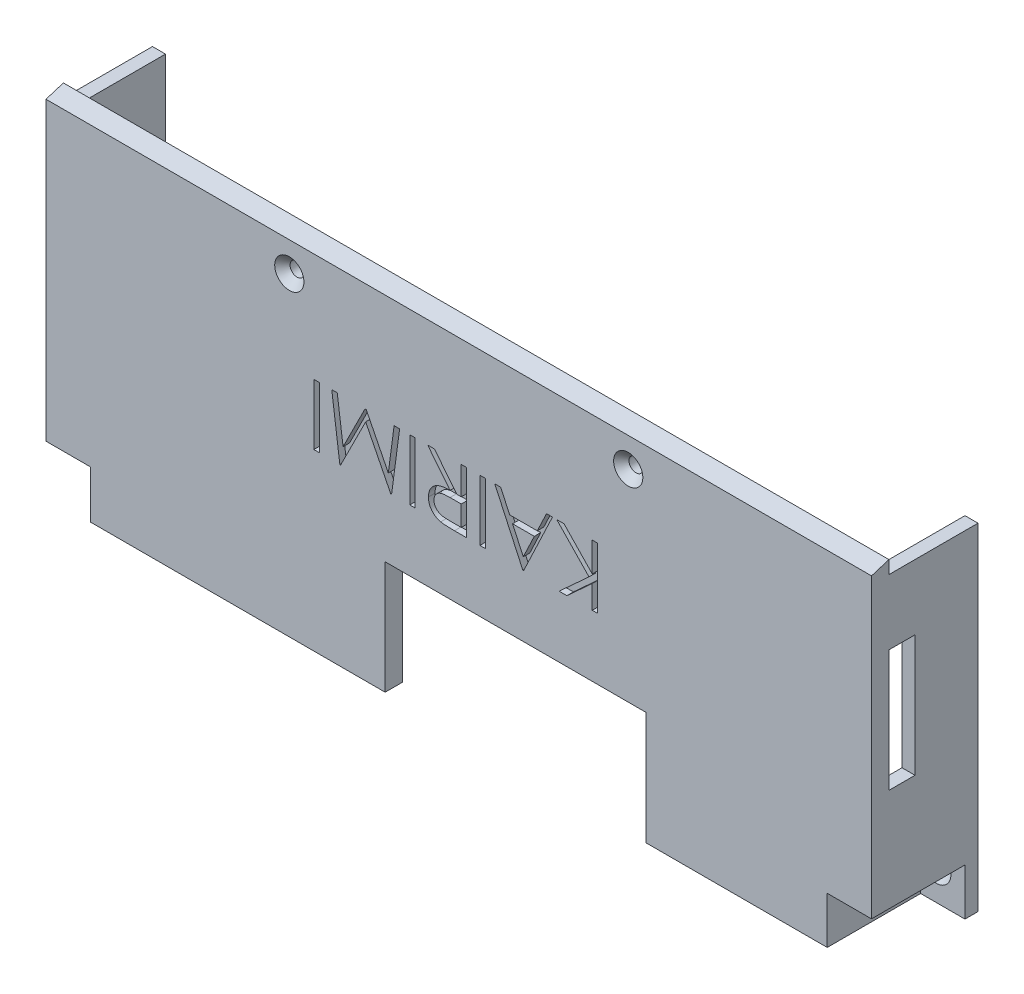
SolidWorks part; units mm, degrees
ref_plane "Alzado" through (0, 0, 0) normal (0, 0, 1) x (1, 0, 0)
ref_plane "Planta" through (0, 0, 0) normal (0, 1, 0) x (1, 0, 0)
ref_plane "Vista lateral" through (0, 0, 0) normal (1, 0, 0) x (0, 0, -1)
sketch "Croquis1" plane through (0, 0, 0) normal (0, 0, 1) x (1, 0, 0)
  line L0 (-32.321, -51.2841) -> (-32.321, 29.1352)
  line L1 (-32.321, 29.1352) -> (157.679, 29.1352)
  line L7 (157.679, 29.1352) -> (157.679, -51.2841)
  line L13 (75.7376, -48.4008) -> (100.7376, -48.4008) construction
  line L16 (-32.321, -51.2841) -> (45.7376, -51.2841)
  line L17 (45.7376, -25.2841) -> (105.7376, -25.2841)
  line L18 (157.679, -51.2841) -> (105.7376, -51.2841)
  line L19 (105.7376, -51.2841) -> (105.7376, -25.2841)
  line L20 (45.7376, -51.2841) -> (45.7376, -25.2841)
  circle A0 centre (23.679, 21.1352) radius 1.625
  circle A1 centre (101.679, 21.1352) radius 1.625
  circle A2 centre (-25.721, -43.8841) radius 1.625
  circle A3 centre (151.079, -44.0841) radius 1.625
  dimension "D1" = 3.25
  dimension "D2" = 23.679
  dimension "D3" = 45.7376
  dimension "D4" = 105.7376
  dimension "D5" = 101.679
  dimension "D6" = 151.079
  dimension "D7" = 157.679
  dimension "D8" = 25.721
  dimension "D9" = 32.321
  dimension "D10" = 21.1352
  dimension "D11" = 29.1352
  dimension "D12" = 25.2841
  dimension "D13" = 43.8841
  dimension "D14" = 44.0841
  dimension "D15" = 48.4008
  dimension "D16" = 51.2841
extrude "Saliente-Extruir1" add sketch "Croquis1" along normal blind 4
sketch "Croquis3" plane through (157.679, 0, 0) normal (1, 0, 0) x (0, 0, -1)
  line L0 (-4, 29.1352) -> (0, 29.1352)
  line L1 (-4, 29.1352) -> (0, 29.1352) construction
  line L2 (0, 29.1352) -> (-4, 27.88)
  line L3 (-4, -51.2841) -> (-4, 29.1352) construction
  line L4 (-4, 27.88) -> (-4, 29.1352)
  dimension "D1" = 1.2552
  dimension "D2" = 29.1352
extrude "Cortar-Extruir1" cut sketch "Croquis3" against normal up to vertex
sketch "Croquis4" plane through (0, 0, 4) normal (0, 0, 1) x (1, 0, 0)
  line L0 (157.679, -51.2841) -> (157.679, 27.88) construction
  line L1 (-32.321, 27.88) -> (157.679, 27.88) construction
  line L2 (-32.321, 27.88) -> (-32.321, -51.2841) construction
  circle A0 centre (23.679, 21.1352) radius 3.36
  circle A1 centre (101.679, 21.1352) radius 3.36
  circle A2 centre (-25.721, -43.8841) radius 3.36
  circle A3 centre (151.079, -44.0841) radius 3.36
  dimension "D1" = 6.7199
  dimension "D2" = 56
  dimension "D3" = 134
  dimension "D4" = 6.7448
  dimension "D5" = 6.6
  dimension "D6" = 183.4
  dimension "D7" = 71.7641
  dimension "D8" = 71.9641
extrude "Cortar-Extruir2" cut sketch "Croquis4" against normal blind 1.8 draft 44
sketch "Croquis5" plane through (0, 0, 0) normal (0, 0, -1) x (-1, 0, 0)
  line L0 (-157.679, -51.2841) -> (-157.679, 29.1352) construction
  line L1 (-154.679, -40.4841) -> (-157.679, -40.4841)
  line L2 (-154.679, -40.4841) -> (-154.679, 26.1352)
  line L3 (-154.679, 26.1352) -> (-157.679, 26.1352)
  line L4 (-157.679, -40.4841) -> (-157.679, 26.1352)
  line L5 (-105.7376, -51.2841) -> (-157.679, -51.2841) construction
  line L6 (29.321, -40.2841) -> (32.321, -40.2841)
  line L7 (29.321, -40.2841) -> (29.321, 26.1352)
  line L8 (29.321, 26.1352) -> (32.321, 26.1352)
  line L9 (32.321, -40.2841) -> (32.321, 26.1352)
  dimension "D1" = 3
  dimension "D2" = 187
  dimension "D3" = 10.8
  dimension "D4" = 11
  dimension "D5" = 77.4194
extrude "Saliente-Extruir2" add sketch "Croquis5" along normal up to vertex (20.5 mm away)
sketch "Croquis7" plane through (0, 0, 0) normal (0, 0, -1) x (-1, 0, 0)
  line L0 (-157.679, 26.1352) -> (-157.679, -40.4841) construction
  line L1 (-157.679, -40.4841) -> (-147.479, -40.4841)
  line L2 (-157.679, -40.4841) -> (-157.679, -51.2841)
  line L3 (-157.679, -51.2841) -> (-147.479, -51.2841)
  line L4 (-147.479, -40.4841) -> (-147.479, -51.2841)
  line L5 (-105.7376, -51.2841) -> (-157.679, -51.2841) construction
  line L6 (29.321, -40.2841) -> (32.321, -40.2841) construction
  line L7 (32.321, -40.2841) -> (22.121, -40.2841)
  line L8 (32.321, -40.2841) -> (32.321, -51.2841)
  line L9 (32.321, -51.2841) -> (22.121, -51.2841)
  line L10 (22.121, -40.2841) -> (22.121, -51.2841)
  line L11 (32.321, -51.2841) -> (-45.7376, -51.2841) construction
  line L12 (32.321, 29.1352) -> (32.321, 26.1352) construction
  line L13 (-157.679, 29.1352) -> (32.321, 29.1352) construction
  dimension "D1" = 10.2
  dimension "D2" = 69.6194
extrude "Cortar-Extruir3" cut sketch "Croquis7" against normal up to vertex (4 mm away)
sketch "Croquis8" plane through (0, 0, 0) normal (0, 0, -1) x (-1, 0, 0)
  line L0 (22.121, -40.2841) -> (22.121, -51.2841) construction
  line L1 (7.321, -47.4841) -> (19.121, -47.4841)
  line L2 (7.321, -47.4841) -> (7.321, -51.2841)
  line L3 (7.321, -51.2841) -> (22.121, -51.2841)
  line L4 (22.121, -47.4841) -> (22.121, -51.2841)
  line L5 (22.121, -51.2841) -> (-45.7376, -51.2841) construction
  line L6 (22.121, -40.2841) -> (19.121, -40.2841) construction
  line L7 (29.321, -40.2841) -> (22.121, -40.2841) construction
  line L8 (22.121, -40.2841) -> (22.121, -37.2841) construction
  line L9 (22.121, -37.2841) -> (29.321, -37.2841)
  line L10 (29.321, 26.1352) -> (29.321, -40.2841) construction
  line L11 (29.321, -37.2841) -> (29.321, -40.2841)
  line L12 (29.321, -40.2841) -> (32.321, -40.2841) construction
  line L13 (29.321, -40.2841) -> (22.121, -40.2841)
  line L14 (22.121, -40.2841) -> (22.121, -47.4841)
  line L15 (22.121, -37.2841) -> (19.121, -37.2841)
  line L16 (19.121, -37.2841) -> (19.121, -40.2841)
  line L17 (19.121, -40.2841) -> (19.121, -47.4841)
  line L18 (-147.479, -51.2841) -> (-147.479, -40.4841) construction
  line L20 (-105.7376, -51.2841) -> (-147.479, -51.2841) construction
  line L21 (-132.679, -47.6841) -> (-144.479, -47.6841)
  line L22 (-132.679, -47.6841) -> (-132.679, -51.2841)
  line L23 (-132.679, -51.2841) -> (-147.479, -51.2841)
  line L24 (-147.479, -47.6841) -> (-147.479, -51.2841)
  line L28 (-147.479, -40.4841) -> (-144.479, -40.4841) construction
  line L29 (-147.479, -40.4841) -> (-154.679, -40.4841) construction
  line L31 (-144.479, -37.2841) -> (-144.479, -40.4841)
  line L32 (-144.479, -40.4841) -> (-144.479, -47.6841)
  line L34 (-147.479, -40.4841) -> (-147.479, -47.6841)
  line L35 (-144.479, -37.2841) -> (-154.679, -37.2841)
  line L36 (-154.679, -40.4841) -> (-154.679, 26.1352) construction
  line L37 (-154.679, -37.2841) -> (-154.679, -40.4841)
  line L38 (-154.679, -40.4841) -> (-147.479, -40.4841)
  dimension "D1" = 154.8
  dimension "D2" = 166.6
extrude "Saliente-Extruir3" add sketch "Croquis8" along normal up to vertex (20.5 mm away)
sketch "Croquis9" plane through (0, 0, -20.5) normal (0, 0, -1) x (-1, 0, 0)
  line L0 (-147.479, -40.4841) -> (-147.479, -51.2841) construction
  line L1 (-147.479, -40.4841) -> (-157.679, -40.4841)
  line L2 (-147.479, -40.4841) -> (-147.479, -51.2841)
  line L3 (-147.479, -51.2841) -> (-157.679, -51.2841)
  line L4 (-157.679, -40.4841) -> (-157.679, -51.2841)
  line L5 (22.121, -51.2841) -> (22.121, -40.2841) construction
  line L6 (22.121, -40.2841) -> (32.321, -40.2841)
  line L7 (22.121, -40.2841) -> (22.121, -51.2841)
  line L8 (22.121, -51.2841) -> (32.321, -51.2841)
  line L9 (32.321, -40.2841) -> (32.321, -51.2841)
  line L10 (7.321, -47.4841) -> (7.321, -51.2841) construction
  line L11 (29.321, -37.2841) -> (19.121, -37.2841) construction
  circle A0 centre (25.721, -43.8841) radius 1.625
  circle A1 centre (-151.079, -44.0841) radius 1.625
  dimension "D1" = 3.25
  dimension "D2" = 18.4
  dimension "D3" = 25
  dimension "D4" = 158.4
  dimension "D5" = 3
  dimension "D6" = 3.2
  dimension "D7" = 6.6
  dimension "D8" = 6.8
  dimension "D9" = 14
extrude "Saliente-Extruir4" add sketch "Croquis9" against normal blind 3
sketch "Croquis10" plane through (0, 0, -17.5) normal (0, 0, 1) x (1, 0, 0)
  line L0 (-22.121, -40.2841) -> (-22.121, -51.2841) construction
  line L1 (-32.321, -40.2841) -> (-22.121, -40.2841) construction
  circle A0 centre (-25.721, -43.8841) radius 3.36
  circle A1 centre (151.079, -44.0841) radius 3.36
  dimension "D1" = 6.7199
  dimension "D2" = 173.2
  dimension "D3" = 3.6
  dimension "D4" = 3.6
  dimension "D5" = 3.8
extrude "Cortar-Extruir4" cut sketch "Croquis10" against normal blind 1.8 draft 44
sketch "Croquis11" plane through (157.679, 0, 0) normal (1, 0, 0) x (0, 0, -1)
  line L0 (0, 26.1352) -> (0, 11.1352) construction
  line L1 (17.5, -40.4841) -> (17.5, -51.2841) construction
  line L2 (0, 11.1352) -> (6, 11.1352)
  line L3 (0, 11.1352) -> (0, -16.8648)
  line L4 (0, -16.8648) -> (6, -16.8648)
  line L5 (6, 11.1352) -> (6, -16.8648)
  line L6 (17.5, -51.2841) -> (20.5, -51.2841) construction
  dimension "D1" = 11.5
  dimension "D2" = 34.4194
extrude "Cortar-Extruir5" cut sketch "Croquis11" against normal blind 3
sketch "Croquis13" plane through (0, 0, 4) normal (0, 0, 1) x (1, 0, 0)
  line L0 (62.679, 27.88) -> (62.679, 2.88) construction
  line L1 (-32.321, 27.88) -> (157.679, 27.88) construction
  line L2 (62.679, 2.88) -> (102.679, 2.88) construction
  line L3 (62.679, 2.88) -> (22.679, 2.88) construction
  line L5 (157.679, -40.4841) -> (157.679, 27.88) construction
  text T0 "KAIRIMI " font "Century Gothic" height 14
  dimension "D1" = 25
  dimension "D2" = 157.679
  dimension "D3" = 27.88
extrude "Cortar-Extruir6" cut sketch "Croquis13" against normal blind 1.5
